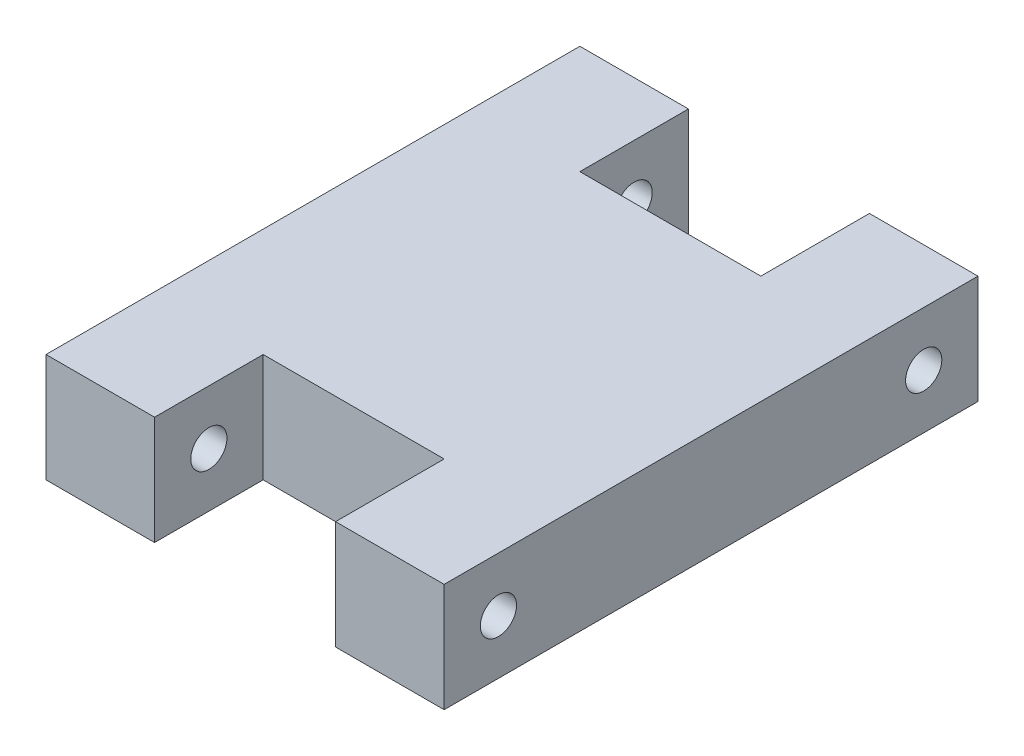
SolidWorks part; units mm, degrees
material "Beech"
ref_plane "Front Plane" through (0, 0, 0) normal (0, 0, 1) x (1, 0, 0)
ref_plane "Top Plane" through (0, 0, 0) normal (0, 1, 0) x (1, 0, 0)
ref_plane "Right Plane" through (0, 0, 0) normal (1, 0, 0) x (0, 0, -1)
sketch "Sketch1" plane through (0, 0, 0) normal (0, 1, 0) x (1, 0, 0)
  line L1 (-22, -29.5) -> (22, -29.5)
  line L2 (-22, -29.5) -> (-22, 29.5)
  line L3 (-22, 29.5) -> (22, 29.5)
  line L4 (22, -29.5) -> (22, 29.5)
  line L5 (-22, -29.5) -> (22, 29.5) construction
  line L6 (-22, 29.5) -> (22, -29.5) construction
  point P0 (0, 0)
  dimension "D1" = 59
  dimension "D2" = 44
extrude "Boss-Extrude1" add sketch "Sketch1" along normal blind 12
sketch "Sketch2" plane through (0, 12, 0) normal (0, 1, 0) x (1, 0, 0)
  line L0 (22, 29.5) -> (-22, 29.5) construction
  line L1 (-10, 29.5) -> (10, 29.5)
  line L2 (-10, 29.5) -> (-10, 17.5)
  line L3 (-10, 17.5) -> (10, 17.5)
  line L4 (10, 29.5) -> (10, 17.5)
  line L5 (-22, -29.5) -> (22, -29.5) construction
  line L6 (-10, -29.5) -> (10, -29.5)
  line L7 (-10, -29.5) -> (-10, -17.5)
  line L8 (-10, -17.5) -> (10, -17.5)
  line L9 (10, -29.5) -> (10, -17.5)
  line L10 (-22, 29.5) -> (-22, -29.5) construction
  line L11 (22, -29.5) -> (22, 29.5) construction
  dimension "D1" = 12
  dimension "D2" = 12
  dimension "D3" = 12
  dimension "D4" = 12
  dimension "D5" = 12
  dimension "D6" = 12
extrude "Cut-Extrude1" cut sketch "Sketch2" against normal up to next
sketch "Sketch3" plane through (-22, 0, 0) normal (-1, 0, 0) x (0, 0, 1)
  line L0 (-29.5, 12) -> (29.5, 12) construction
  line L1 (-29.5, 12) -> (-29.5, 0) construction
  circle A0 centre (-23.5, 6) radius 2
  dimension "D2" = 4
  dimension "D1" = 6
  dimension "D3" = 6
extrude "Cut-Extrude2" cut sketch "Sketch3" against normal up to surface (44 mm away) up to face at (22, 6, 0)
mirror "Mirror1" about plane through (0, 0, 0) normal (0, 0, 1) of "Cut-Extrude2"
